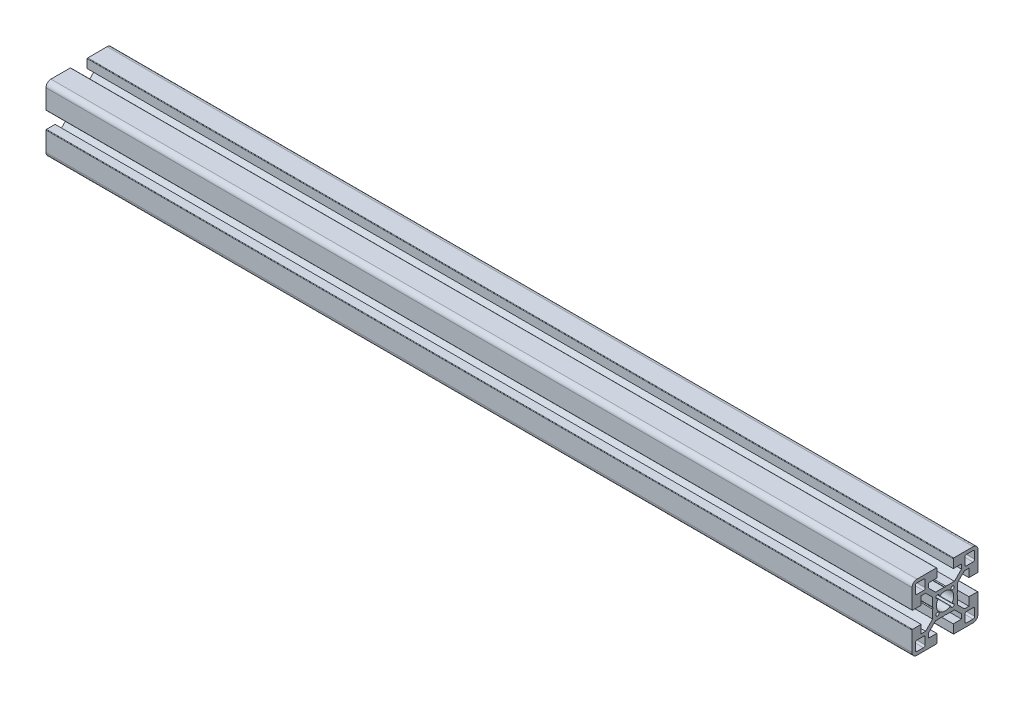
SolidWorks part; units mm, degrees
ref_plane "Front Plane" through (0, 0, 0) normal (0, 0, 1) x (1, 0, 0)
ref_plane "Top Plane" through (0, 0, 0) normal (0, 1, 0) x (1, 0, 0)
ref_plane "Right Plane" through (0, 0, 0) normal (1, 0, 0) x (0, 0, -1)
sketch "Sketch1" plane through (0, 0, 0) normal (0, 1, 0) x (1, 0, 0)
  line L0 (0, 0) -> (525, 0)
  dimension "D1" = 525
other "Structural Member2"
ref_plane "Plane3" through (0, 0, 0) normal (1, 0, 0) x (0, 0, -1)
sketch "Profile" plane through (0, 0, 0) normal (1, 0, 0) x (0, 0, -1)
  line L11 (37, 68) -> (33, 68)
  line L12 (69.7, 55) -> (64.5, 55)
  line L13 (64.5, 60) -> (64.5, 55)
  line L14 (70, 67) -> (70, 55.3)
  line L15 (68, 67) -> (68, 63)
  line L16 (64.5, 40) -> (64.5, 45)
  line L17 (69.7, 45) -> (64.5, 45)
  line L18 (70, 33) -> (70, 44.7)
  line L19 (68, 33) -> (68, 37)
  line L20 (33, 70) -> (44.7, 70)
  line L21 (60, 64.5) -> (60, 61.7678)
  line L22 (60, 64.5) -> (55, 64.5)
  line L23 (60, 61.7678) -> (55.7322, 57.5)
  line L24 (61.7678, 60) -> (57.5, 55.7322)
  line L25 (40, 64.5) -> (40, 61.7678)
  line L26 (40, 64.5) -> (45, 64.5)
  line L27 (40, 61.7678) -> (44.2678, 57.5)
  line L28 (35.5, 60) -> (38.2322, 60)
  line L29 (30.3, 55) -> (35.5, 55)
  line L30 (38.2322, 60) -> (42.5, 55.7322)
  line L31 (35.5, 55) -> (35.5, 60)
  line L32 (30, 67) -> (30, 55.3)
  line L33 (32, 67) -> (32, 63)
  line L34 (38, 67) -> (38, 63)
  line L35 (45, 69.7) -> (45, 64.5)
  line L36 (55, 69.7) -> (55, 64.5)
  line L37 (62, 67) -> (62, 63)
  line L38 (61.7678, 40) -> (57.5, 44.2678)
  line L39 (60, 35.5) -> (60, 38.2322)
  line L40 (60, 38.2322) -> (55.7322, 42.5)
  line L41 (55, 30.3) -> (55, 35.5)
  line L42 (62, 33) -> (62, 37)
  line L43 (38.2322, 40) -> (42.5, 44.2678)
  line L44 (40, 35.5) -> (40, 38.2322)
  line L45 (40, 35.5) -> (45, 35.5)
  line L46 (44.2678, 42.5) -> (49.4804, 42.5)
  line L47 (40, 38.2322) -> (44.2678, 42.5)
  line L48 (35.5, 45) -> (35.5, 40)
  line L49 (30.3, 45) -> (35.5, 45)
  line L50 (33, 38) -> (37, 38)
  line L51 (35.5, 40) -> (38.2322, 40)
  line L52 (33, 32) -> (37, 32)
  line L53 (33, 30) -> (44.7, 30)
  line L54 (30, 33) -> (30, 44.7)
  line L55 (32, 33) -> (32, 37)
  line L56 (38, 33) -> (38, 37)
  line L57 (45, 30.3) -> (45, 35.5)
  line L58 (50, 70) -> (50, 30) construction
  line L59 (57.5, 55.7322) -> (57.5, 50.5196)
  line L60 (67, 38) -> (63, 38)
  line L61 (30, 50) -> (70, 50) construction
  line L62 (64.5, 40) -> (61.7678, 40)
  line L63 (67, 62) -> (63, 62)
  line L64 (64.5, 60) -> (61.7678, 60)
  line L65 (42.5, 44.2678) -> (42.5, 49.4804)
  line L66 (37, 62) -> (33, 62)
  line L67 (44.2678, 57.5) -> (49.4804, 57.5)
  line L68 (57.5, 49.4804) -> (57.5, 44.2678)
  line L69 (42.5, 50.5196) -> (42.5, 55.7322)
  line L70 (50.5196, 57.5) -> (55.7322, 57.5)
  line L71 (55.3, 70) -> (67, 70)
  line L72 (63, 68) -> (67, 68)
  line L73 (55.3, 30) -> (67, 30)
  line L74 (63, 32) -> (67, 32)
  line L75 (55, 35.5) -> (60, 35.5)
  line L76 (50.5196, 42.5) -> (55.7322, 42.5)
  line L77 (57.2, 50) -> (57.5, 50.5196)
  line L78 (57.2, 50) -> (57.5, 49.4804)
  line L79 (42.8, 50) -> (42.5, 50.5196)
  line L80 (42.8, 50) -> (42.5, 49.4804)
  line L81 (50, 57.2) -> (49.4804, 57.5)
  line L82 (50, 57.2) -> (50.5196, 57.5)
  line L83 (50, 42.8) -> (49.4804, 42.5)
  line L84 (50, 42.8) -> (50.5196, 42.5)
  arc A0 (69.7, 55) -> (70, 55.3) centre (69.7, 55.3) ccw
  arc A1 (68, 67) -> (67, 68) centre (67, 67) ccw
  arc A2 (70, 44.7) -> (69.7, 45) centre (69.7, 44.7) ccw
  arc A3 (68, 37) -> (67, 38) centre (67, 37) ccw
  arc A4 (62, 63) -> (63, 62) centre (63, 63) ccw
  arc A5 (30, 55.3) -> (30.3, 55) centre (30.3, 55.3) ccw
  arc A6 (37, 62) -> (38, 63) centre (37, 63) ccw
  arc A7 (38, 67) -> (37, 68) centre (37, 67) ccw
  arc A8 (62, 33) -> (63, 32) centre (63, 33) ccw
  arc A9 (30.3, 45) -> (30, 44.7) centre (30.3, 44.7) ccw
  arc A10 (38, 37) -> (37, 38) centre (37, 37) ccw
  arc A11 (32, 33) -> (33, 32) centre (33, 33) ccw
  arc A12 (37, 32) -> (38, 33) centre (37, 33) ccw
  arc A13 (33, 38) -> (32, 37) centre (33, 37) ccw
  arc A14 (63, 38) -> (62, 37) centre (63, 37) ccw
  arc A15 (67, 62) -> (68, 63) centre (67, 63) ccw
  arc A16 (30, 33) -> (33, 30) centre (33, 33) ccw
  arc A17 (44.7, 30) -> (45, 30.3) centre (44.7, 30.3) ccw
  arc A18 (32, 63) -> (33, 62) centre (33, 63) ccw
  arc A19 (33, 68) -> (32, 67) centre (33, 67) ccw
  arc A20 (45, 69.7) -> (44.7, 70) centre (44.7, 69.7) ccw
  arc A21 (33, 70) -> (30, 67) centre (33, 67) ccw
  arc A22 (63, 68) -> (62, 67) centre (63, 67) ccw
  arc A23 (67, 32) -> (68, 33) centre (67, 33) ccw
  arc A24 (55, 30.3) -> (55.3, 30) centre (55.3, 30.3) ccw
  arc A25 (55.3, 70) -> (55, 69.7) centre (55.3, 69.7) ccw
  arc A26 (67, 30) -> (70, 33) centre (67, 33) ccw
  arc A27 (70, 67) -> (67, 70) centre (67, 67) ccw
  arc A28 (45.694, 53.0035) -> (45.694, 46.9966) centre (50, 50) ccw
  arc A29 (46.9981, 45.6929) -> (53.0039, 45.6943) centre (50, 50) ccw
  arc A30 (54.3061, 46.9967) -> (54.3061, 53.0034) centre (50, 50) ccw
  arc A31 (53.0033, 54.3061) -> (46.9968, 54.3062) centre (50, 50) ccw
  arc A32 (46.4038, 54.6058) -> (45.3944, 53.5962) centre (45.4038, 54.5962) ccw
  arc A33 (54.608, 53.5963) -> (53.5962, 54.6065) centre (54.5962, 54.5962) ccw
  arc A34 (53.5962, 45.3942) -> (54.6061, 46.4038) centre (54.5962, 45.4038) ccw
  arc A35 (45.3939, 46.4038) -> (46.4038, 45.3942) centre (45.4038, 45.4038) ccw
  arc A36 (45.694, 53.0035) -> (45.3944, 53.5962) centre (45.3778, 53.2158) ccw
  arc A37 (46.4038, 54.6058) -> (46.9968, 54.3062) centre (46.7842, 54.6222) ccw
  arc A38 (54.608, 53.5963) -> (54.3061, 53.0034) centre (54.6221, 53.2158) ccw
  arc A39 (53.0033, 54.3061) -> (53.5962, 54.6065) centre (53.2158, 54.6221) ccw
  arc A40 (45.3939, 46.4038) -> (45.694, 46.9966) centre (45.3778, 46.7842) ccw
  arc A41 (46.9981, 45.6929) -> (46.4038, 45.3942) centre (46.7842, 45.3779) ccw
  arc A42 (54.3061, 46.9967) -> (54.6061, 46.4038) centre (54.6222, 46.7842) ccw
  arc A43 (53.5962, 45.3942) -> (53.0039, 45.6943) centre (53.2158, 45.3778) ccw
  point P109 (30, 70)
  point P110 (30, 30)
  point P111 (70, 30)
  point P112 (70, 70)
  point P113 (0, 0)
